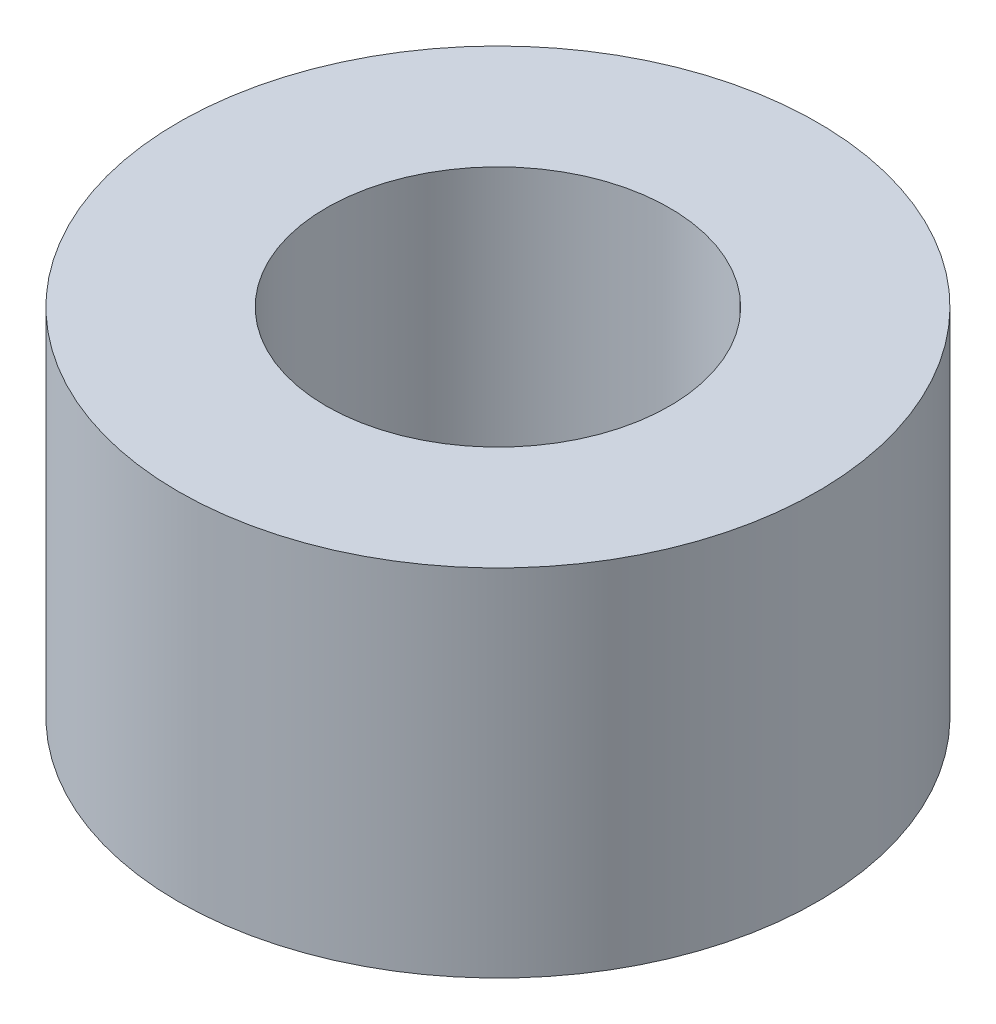
SolidWorks part; units mm, degrees
ref_plane "Front Plane" through (0, 0, 0) normal (0, 0, 1) x (1, 0, 0)
ref_plane "Top Plane" through (0, 0, 0) normal (0, 1, 0) x (1, 0, 0)
ref_plane "Right Plane" through (0, 0, 0) normal (1, 0, 0) x (0, 0, -1)
sketch "Sketch1" plane through (0, 0, 0) normal (0, 1, 0) x (1, 0, 0)
  circle A0 centre (0, 0) radius 27
  circle A1 centre (0, 0) radius 14.5
  dimension "D1" = 54
  dimension "D2" = 29
extrude "Boss-Extrude1" add sketch "Sketch1" along normal blind 30
